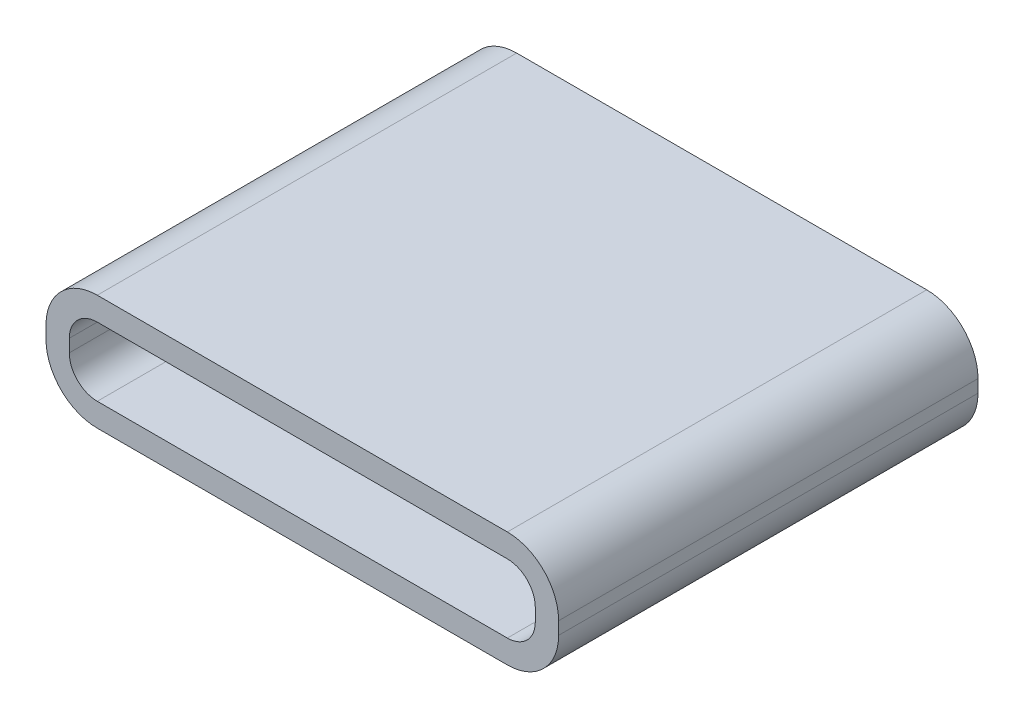
SolidWorks part; units mm, degrees
ref_plane "Front Plane" through (0, 0, 0) normal (0, 0, 1) x (1, 0, 0)
ref_plane "Top Plane" through (0, 0, 0) normal (0, 1, 0) x (1, 0, 0)
ref_plane "Right Plane" through (0, 0, 0) normal (1, 0, 0) x (0, 0, -1)
sketch "Sketch1" plane through (0, 0, 0) normal (0, 0, 1) x (1, 0, 0)
  line L8 (5, 73.5812) -> (445, 73.5812)
  line L9 (500, 18.5812) -> (500, 5)
  line L10 (5, -50) -> (445, -50)
  line L11 (-50, 18.5812) -> (-50, 5)
  line L12 (5, 48.5812) -> (445, 48.5812)
  line L13 (475, 18.5812) -> (475, 5)
  line L14 (5, -25) -> (445, -25)
  line L15 (-25, 18.5812) -> (-25, 5)
  arc A8 (500, 18.5812) -> (445, 73.5812) centre (445, 18.5812) ccw
  arc A9 (500, 5) -> (445, -50) centre (445, 5) cw
  arc A10 (5, -50) -> (-50, 5) centre (5, 5) cw
  arc A11 (-50, 18.5812) -> (5, 73.5812) centre (5, 18.5812) cw
  arc A12 (475, 18.5812) -> (445, 48.5812) centre (445, 18.5812) ccw
  arc A13 (475, 5) -> (445, -25) centre (445, 5) cw
  arc A14 (5, -25) -> (-25, 5) centre (5, 5) cw
  arc A15 (-25, 18.5812) -> (5, 48.5812) centre (5, 18.5812) cw
  point P11 (0, 0)
extrude "Boss-Extrude1" add sketch "Sketch1" along normal blind 450
